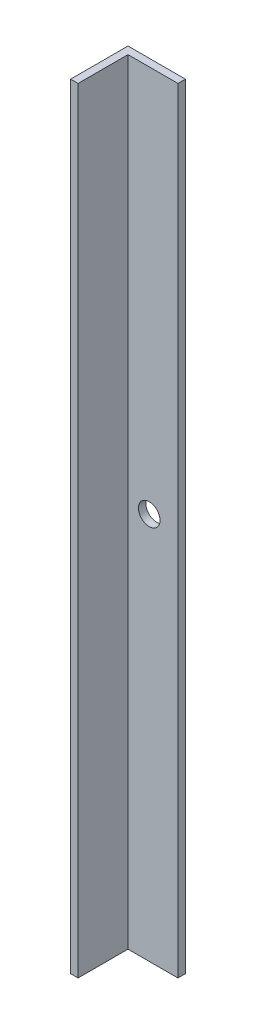
SolidWorks part; units mm, degrees
ref_plane "Front Plane" through (0, 0, 0) normal (0, 0, 1) x (1, 0, 0)
ref_plane "Top Plane" through (0, 0, 0) normal (0, 1, 0) x (1, 0, 0)
ref_plane "Right Plane" through (0, 0, 0) normal (1, 0, 0) x (0, 0, -1)
sketch "Sketch1" plane through (0, 0, 0) normal (0, 1, 0) x (1, 0, 0)
  line L0 (0, 0) -> (3.302, 0)
  line L5 (3.302, 0) -> (3.302, 22.098)
  line L7 (0, 25.4) -> (0, 0)
  line L8 (0, 25.4) -> (25.4, 25.4)
  line L9 (3.302, 22.098) -> (25.4, 22.098)
  line L10 (25.4, 25.4) -> (25.4, 22.098)
  point P1 (0, 0)
  point P6 (3.302, 0)
  dimension "D3" = 25.4
  dimension "D5" = 3.302
  dimension "D4" = 3.302
extrude "Boss-Extrude1" add sketch "Sketch1" along normal blind 342.9
sketch "Sketch2" plane through (0, 0, -25.4) normal (0, 0, -1) x (-1, 0, 0)
  line L0 (-12.7, 0) -> (-12.7, 342.9) construction
  line L1 (-25.4, 0) -> (0, 0) construction
  line L2 (-25.4, 342.9) -> (0, 342.9) construction
  circle A0 centre (-12.7, 171.45) radius 4.7625
  dimension "D1" = 9.525
extrude "Cut-Extrude1" cut sketch "Sketch2" against normal up to next
equation "\"D5@Sketch1\"=\"D4@Sketch1\""
